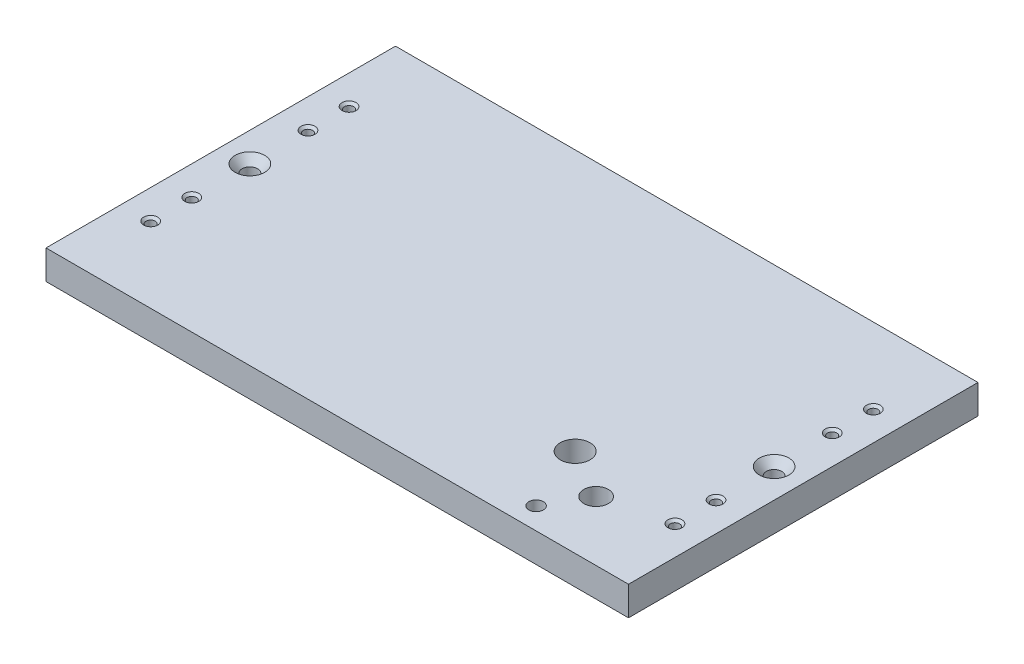
SolidWorks part; units mm, degrees
material "6061 Alloy"
ref_plane "Front Plane" through (0, 0, 0) normal (0, 0, 1) x (1, 0, 0)
ref_plane "Top Plane" through (0, 0, 0) normal (0, 1, 0) x (1, 0, 0)
ref_plane "Right Plane" through (0, 0, 0) normal (1, 0, 0) x (0, 0, -1)
sketch "Sketch1" plane through (0, 0, 0) normal (0, 1, 0) x (1, 0, 0)
  line L1 (-127, -76.2) -> (127, -76.2)
  line L2 (-127, -76.2) -> (-127, 76.2)
  line L3 (-127, 76.2) -> (127, 76.2)
  line L4 (127, -76.2) -> (127, 76.2)
  line L5 (-127, -76.2) -> (127, 76.2) construction
  line L6 (-127, 76.2) -> (127, -76.2) construction
  point P4 (0, 0)
  dimension "D1" = 254
  dimension "D2" = 152.4
extrude "Boss-Extrude1" add sketch "Sketch1" along normal blind 12.7
sketch "Sketch2" plane through (0, 12.7, 0) normal (0, 1, 0) x (1, 0, 0)
  line L0 (-127, -76.2) -> (127, -76.2) construction
  line L1 (-101.6, -76.2) -> (101.6, -76.2)
  line L2 (-101.6, -76.2) -> (-101.6, -12.7)
  line L3 (-101.6, -12.7) -> (101.6, -12.7)
  line L4 (101.6, -76.2) -> (101.6, -12.7)
  line L5 (-101.6, -76.2) -> (101.6, -12.7) construction
  line L6 (-101.6, -12.7) -> (101.6, -76.2) construction
  line L7 (127, 76.2) -> (-127, 76.2) construction
  line L8 (101.6, 76.2) -> (-101.6, 76.2)
  line L9 (101.6, 76.2) -> (101.6, 12.7)
  line L10 (101.6, 12.7) -> (-101.6, 12.7)
  line L11 (-101.6, 76.2) -> (-101.6, 12.7)
  line L12 (101.6, 76.2) -> (-101.6, 12.7) construction
  line L13 (101.6, 12.7) -> (-101.6, 76.2) construction
  line L14 (-127, 76.2) -> (-127, -76.2) construction
  line L15 (127, -76.2) -> (127, 76.2) construction
  point P4 (0, -44.45)
  point P11 (0, 44.45)
  dimension "D1" = 25.4
  dimension "D2" = 25.4
  dimension "D3" = 25.4
extrude "Cut-Extrude1" cut sketch "Sketch2" against normal through all
sketch "Sketch3" plane through (0, 12.7, 0) normal (0, 1, 0) x (1, 0, 0)
  line L0 (-114.3, -43.2435) -> (-114.3, -76.2) construction
  line L1 (-127, -76.2) -> (-101.6, -76.2) construction
  line L2 (-114.3, -43.2435) -> (-114.3, -25.3365) construction
  circle A0 centre (-114.3, -25.3365) radius 2.0193
  circle A1 centre (-114.3, -43.2435) radius 2.0193
  dimension "D3" = 4.0386
  dimension "D1" = 32.9565
  dimension "D2" = 17.907
sketch "Sketch8" plane through (0, 12.7, 0) normal (0, 1, 0) x (1, 0, 0)
  circle A0 centre (39.9999, 0) radius 2.8378
  point P0 (0, 0)
  dimension "D1" = 39.9999
extrude "Cut-Extrude4" [suppressed] cut sketch "Sketch8" against normal through all
sketch "Sketch9" [suppressed] plane through (0, 12.7, 0) normal (0, 1, 0) x (1, 0, 0)
  line L0 (34.9199, -9.525) -> (34.9199, -12.7) construction
  line L1 (34.9199, 9.525) -> (50.7949, 9.525)
  line L2 (34.9199, 9.525) -> (34.9199, -9.525)
  line L3 (34.9199, -9.525) -> (50.7949, -9.525)
  line L4 (50.7949, 9.525) -> (50.7949, -9.525)
  line L5 (34.9199, 9.525) -> (50.7949, -9.525) construction
  line L6 (34.9199, -9.525) -> (50.7949, 9.525) construction
  line L7 (101.6, -12.7) -> (-101.6, -12.7) construction
  line L8 (34.9199, 9.525) -> (34.9199, 12.7) construction
  line L9 (-101.6, 12.7) -> (101.6, 12.7) construction
  circle A0 centre (39.9999, 0) radius 2.8378 construction
  point P4 (42.8574, 0)
  dimension "D2" = 5.08
  dimension "D1" = 15.875
  dimension "D3" = 19.05
extrude "Cut-Extrude5" [suppressed] cut sketch "Sketch9" against normal blind 1.5875
sketch "Sketch10" [suppressed] plane through (0, 12.7, 0) normal (0, 1, 0) x (1, 0, 0)
  circle A0 centre (34.9199, 9.525) radius 1.5875
  circle A1 centre (34.9199, -9.525) radius 1.5875
  circle A2 centre (50.7949, -9.525) radius 1.5875
  circle A3 centre (50.7949, 9.525) radius 1.5875
  dimension "D1" = 3.175
extrude "Cut-Extrude6" [suppressed] cut sketch "Sketch10" against normal up to surface (1.5875 mm away)
sketch "Sketch11" plane through (0, 12.7, 0) normal (0, 1, 0) x (1, 0, 0)
  line L1 (-101.6, 76.2) -> (101.6, 76.2)
  line L2 (-101.6, 76.2) -> (-101.6, 12.7)
  line L3 (-101.6, 12.7) -> (101.6, 12.7)
  line L4 (101.6, 76.2) -> (101.6, 12.7)
  line L5 (-101.6, 76.2) -> (101.6, 12.7) construction
  line L6 (-101.6, 12.7) -> (101.6, 76.2) construction
  line L7 (101.6, -12.7) -> (-101.6, -12.7)
  line L8 (101.6, -12.7) -> (101.6, -76.2)
  line L9 (101.6, -76.2) -> (-101.6, -76.2)
  line L10 (-101.6, -12.7) -> (-101.6, -76.2)
  line L11 (101.6, -12.7) -> (-101.6, -76.2) construction
  line L12 (101.6, -76.2) -> (-101.6, -12.7) construction
  point P4 (0, 44.45)
  point P11 (0, -44.45)
extrude "Boss-Extrude2" add sketch "Sketch11" against normal up to surface (12.7 mm away) up to face at (0, 0, 0)
sketch "Sketch12" plane through (0, 12.7, 0) normal (0, 1, 0) x (1, 0, 0)
  line L0 (0, 0) -> (12.7, 0) construction
  line L1 (0, 0) -> (-12.7, 0) construction
  circle A0 centre (12.7, 0) radius 1.1303
  circle A1 centre (-12.7, 0) radius 1.1303
  dimension "D1" = 2.2606
  dimension "D2" = 12.7
extrude "Cut-Extrude7" [suppressed] cut sketch "Sketch12" against normal through all
sketch "Sketch13" plane through (0, 12.7, 0) normal (0, 1, 0) x (1, 0, 0)
  line L0 (0, 0) -> (86.819, -50.125) construction
  line L1 (0, 0) -> (127, 0) construction
  line L2 (127, -76.2) -> (127, 76.2) construction
  circle A0 centre (86.819, -50.125) radius 5.3578
  circle A1 centre (65.1684, -37.625) radius 6.4897
  point P0 (0, 0)
  point P1 (65.1684, -37.625)
  point P3 (86.819, -50.125)
  dimension "D4" = 10.7156
  dimension "D5" = 12.9794
  dimension "D1" = 75.25
  dimension "D2" = 25
  dimension "D3" = 30
extrude "Cut-Extrude8" cut sketch "Sketch13" against normal through all
sketch "Sketch14" plane through (0, 12.7, 0) normal (0, 1, 0) x (1, 0, 0)
  line L0 (65.1684, -37.625) -> (86.819, -50.125) construction
  line L1 (86.819, -50.125) -> (78.819, -63.9814) construction
  line L2 (78.819, -63.9814) -> (77.2379, -66.72) construction
  circle A0 centre (77.2379, -66.72) radius 3.1623
  dimension "D2" = 6.3246
  dimension "D1" = 16
extrude "Cut-Extrude9" cut sketch "Sketch14" against normal through all
hole_wizard "#10-32 Tapped Hole2" positions "Sketch17" profile "Sketch18" tap size "#10-32" standard "ANSI Inch" end condition through all
sketch "Sketch17" plane through (0, 12.7, 0) normal (0, 1, 0) x (1, 0, 0)
  point P0 (-114.3, -25.3365)
  point P3 (-114.3, -43.2435)
sketch "Sketch18" plane through (-114.3, 12.7, 25.3365) normal (1, 0, 0) x (0, 0, 1)
  line L0 (0, 0) -> (0, 12.7)
  line L1 (0, 12.7) -> (2.0193, 12.7)
  line L2 (2.0193, 12.7) -> (2.0193, 1.0287)
  line L3 (2.0193, 1.0287) -> (3.048, 0)
  line L5 (3.048, 0) -> (0, 0)
  line L6 (-2.0193, 1.0287) -> (-3.048, 0) construction
  line L11 (0, -6.35) -> (0, 107.95) construction
  dimension "Thru Tap Drill Dia." = 4.0386
  dimension "Thru Tap Drill Depth" = 12.7
  dimension "Near C'Sink Dia." = 6.096
  dimension "Near C'Sink Angle" = 90
cosmetic thread "Hole Thread3"
cosmetic thread "Hole Thread4"
mirror "Mirror1" about plane through (0, 0, 0) normal (0, 0, 1) of "#10-32 Tapped Hole2"
mirror "Mirror2" about plane through (0, 0, 0) normal (1, 0, 0) of "#10-32 Tapped Hole2", "Mirror1"
sketch "Sketch19" plane through (0, 12.7, 0) normal (0, 1, 0) x (1, 0, 0)
  line L0 (-114.3, 25.3365) -> (-114.3, 0) construction
  line L1 (-114.3, 0) -> (-114.3, -25.3365) construction
hole_wizard "CSK for 1/4 Flat Head Machine Screw1" positions "Sketch20" profile "Sketch21" countersink size "1/4" standard "ANSI Inch" end condition through all
sketch "Sketch20" plane through (0, 12.7, 0) normal (0, 1, 0) x (1, 0, 0)
  point P0 (-114.3, 0)
sketch "Sketch21" plane through (-114.3, 12.7, 0) normal (1, 0, 0) x (0, 0, 1)
  line L0 (0, 0) -> (0, 12.7)
  line L1 (0, 12.7) -> (3.3782, 12.7)
  line L2 (3.3782, 12.7) -> (3.3782, 3.5209)
  line L3 (3.3782, 3.5209) -> (6.4389, 0)
  line L5 (6.4389, 0) -> (0, 0)
  line L6 (-3.3782, 3.5209) -> (-6.4389, 0) construction
  line L11 (0, -6.35) -> (0, 107.95) construction
  dimension "Thru Hole Dia." = 6.7564
  dimension "Thru Hole Depth" = 12.7
  dimension "Near C'Sink Dia." = 12.8778
  dimension "Near C'Sink Angle" = 82
mirror "Mirror3" about plane through (0, 0, 0) normal (1, 0, 0) of "CSK for 1/4 Flat Head Machine Screw1"
sketch3d "Sketch_MAC1-1_ONEPIECE_BASE_MILLING_1" [suppressed]
  line L0 (-127, 12.7, 76.2) -> (-117, 12.7, 76.2)
  line L1 (-127, 12.7, 76.2) -> (-127, 12.7, 66.2)
  point P0 (-127, 12.7, 76.2)
  point P1 (-117, 12.7, 76.2)
  point P2 (-127, 12.7, 66.2)
equation "\"A\"=3.03281"
equation "\"wing_spar_height\"= 2"
equation "\"wing_spar_thickness\"= .5"
equation "\"frame_width\"= 10"
equation "\"load_length\"= 130mm"
equation "\"load_width\"= 32mm"
equation "\"load_hole_space\"= 75.25mm"
equation "\"D1@Sketch13\"=\"load_hole_space\""
equation "\"load_hole_space_2\"= 25mm"
equation "\"D2@Sketch13\"=\"load_hole_space_2\""
equation "\"D1@Sketch14\"=\"load_width\"/2"
